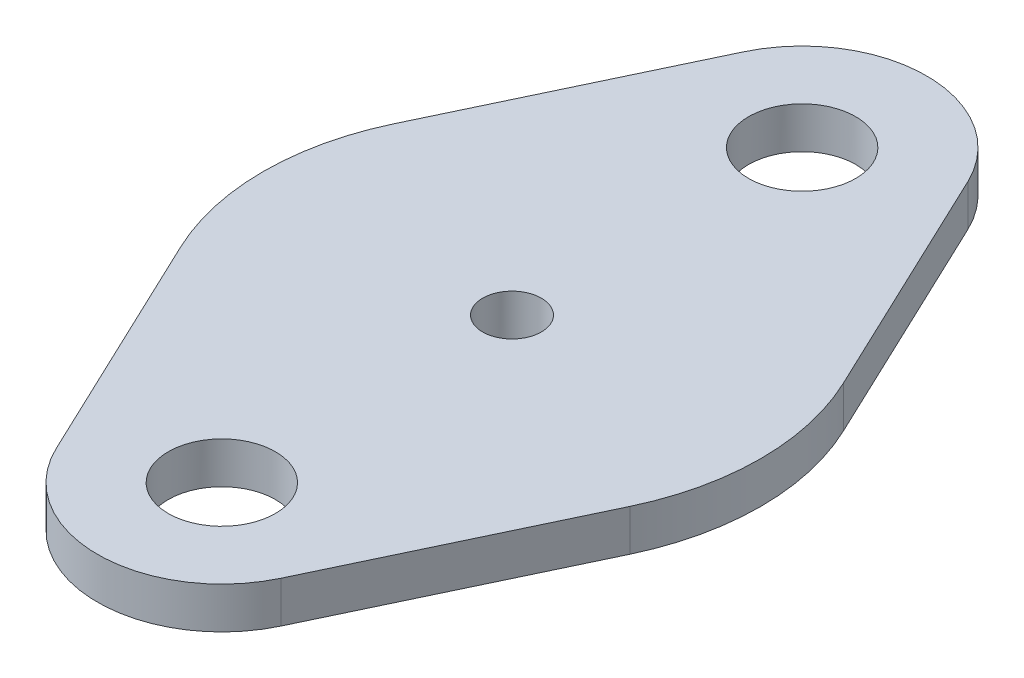
SolidWorks part; units mm, degrees
ref_plane "Front Plane" through (0, 0, 0) normal (0, 0, 1) x (1, 0, 0)
ref_plane "Top Plane" through (0, 0, 0) normal (0, 1, 0) x (1, 0, 0)
ref_plane "Right Plane" through (0, 0, 0) normal (1, 0, 0) x (0, 0, -1)
sketch "Sketch1" plane through (0, 0, 0) normal (0, 1, 0) x (1, 0, 0)
  line L1 (0, 0) -> (38.1, 0)
  line L2 (0, 0) -> (0, 63.5)
  line L3 (0, 63.5) -> (38.1, 63.5)
  line L4 (38.1, 0) -> (38.1, 63.5)
  dimension "D1" = 38.1
  dimension "D2" = 63.5
extrude "Boss-Extrude1" add sketch "Sketch1" along normal blind 3.175
hole_wizard "#8 Clearance Hole1" positions "Sketch2" profile "Sketch3" hole size "#8" standard "ANSI Inch" end condition up to next
sketch "Sketch2" plane through (0, 3.175, 0) normal (0, 1, 0) x (1, 0, 0)
  line L0 (0, 63.5) -> (38.1, 0) construction
  line L1 (0, 0) -> (38.1, 0) construction
  point P6 (19.05, 31.75)
sketch "Sketch3" plane through (19.05, 3.175, -31.75) normal (1, 0, 0) x (0, 0, 1)
  line L0 (0, 0) -> (0, 3.175)
  line L1 (0, 3.175) -> (2.2479, 3.175)
  line L2 (2.2479, 3.175) -> (2.2479, 0)
  line L5 (2.2479, 0) -> (0, 0)
  line L11 (0, -6.35) -> (0, 107.95) construction
  dimension "Thru Hole Dia." = 4.4958
  dimension "Thru Hole Depth" = 3.175
hole_wizard "5/16 Clearance Hole1" positions "Sketch4" profile "Sketch5" hole size "5/16" standard "ANSI Inch" end condition up to next
sketch "Sketch4" plane through (0, 3.175, 0) normal (0, 1, 0) x (1, 0, 0)
  line L1 (19.05, 63.5) -> (19.05, 0) construction
  line L2 (38.1, 63.5) -> (0, 63.5) construction
  line L3 (0, 0) -> (38.1, 0) construction
  circle A0 centre (19.05, 31.75) radius 2.2479 construction
  point P11 (19.05, 53.975)
  point P13 (19.05, 9.525)
  dimension "D1" = 22.225
  dimension "D2" = 22.225
sketch "Sketch5" plane through (19.05, 3.175, -9.525) normal (1, 0, 0) x (0, 0, 1)
  line L0 (0, 0) -> (0, 3.175)
  line L1 (0, 3.175) -> (4.1021, 3.175)
  line L2 (4.1021, 3.175) -> (4.1021, 0)
  line L5 (4.1021, 0) -> (0, 0)
  line L11 (0, -6.35) -> (0, 107.95) construction
  dimension "Thru Hole Dia." = 8.2042
  dimension "Thru Hole Depth" = 3.175
sketch "Sketch6" plane through (0, 3.175, 0) normal (0, 1, 0) x (1, 0, 0)
  line L0 (27.6559, 58.0571) -> (36.2618, 39.9143)
  line L1 (38.1, 0) -> (38.1, 63.5) construction
  line L2 (38.1, 63.5) -> (0, 63.5) construction
  line L3 (36.2618, 23.5857) -> (27.6559, 5.4429)
  line L4 (10.4441, 58.0571) -> (1.8382, 39.9143)
  line L5 (1.8382, 23.5857) -> (10.4441, 5.4429)
  line L6 (0, 0) -> (38.1, 0) construction
  line L20 (-1.27, -1.27) -> (39.37, -1.27)
  line L21 (-1.27, -1.27) -> (-1.27, 64.77)
  line L22 (-1.27, 64.77) -> (39.37, 64.77)
  line L23 (39.37, -1.27) -> (39.37, 64.77)
  line L24 (-1.27, -1.27) -> (39.37, 64.77) construction
  line L25 (-1.27, 64.77) -> (39.37, -1.27) construction
  arc A0 (27.6559, 58.0571) -> (10.4441, 58.0571) centre (19.05, 53.975) ccw
  arc A1 (1.8382, 39.9143) -> (1.8382, 23.5857) centre (19.05, 31.75) ccw
  arc A2 (10.4441, 5.4429) -> (27.6559, 5.4429) centre (19.05, 9.525) ccw
  arc A3 (36.2618, 23.5857) -> (36.2618, 39.9143) centre (19.05, 31.75) ccw
  dimension "D1" = 66.04
  dimension "D2" = 40.64
extrude "Cut-Extrude1" cut sketch "Sketch6" against normal blind 3.175
